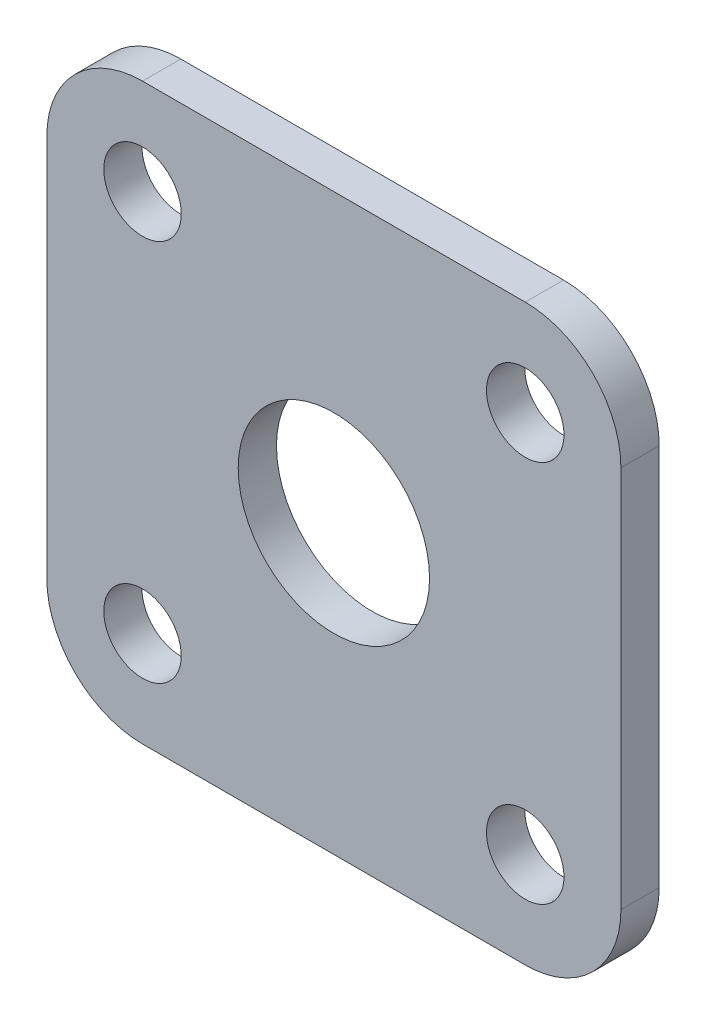
SolidWorks part; units mm, degrees
material "AISI 304"
ref_plane "Front Plane" through (0, 0, 0) normal (0, 0, 1) x (1, 0, 0)
ref_plane "Top Plane" through (0, 0, 0) normal (0, 1, 0) x (1, 0, 0)
ref_plane "Right Plane" through (0, 0, 0) normal (1, 0, 0) x (0, 0, -1)
sketch "Sketch1" plane through (0, 0, 0) normal (0, 0, 1) x (1, 0, 0)
  line L1 (-10, 15) -> (10, 15)
  line L2 (-15, 10) -> (-15, -10)
  line L3 (-10, -15) -> (10, -15)
  line L4 (15, 10) -> (15, -10)
  line L5 (-15, 15) -> (15, -15) construction
  line L6 (-15, -15) -> (15, 15) construction
  line L7 (-10, 10) -> (10, 10) construction
  line L8 (-10, 10) -> (-10, -10) construction
  line L9 (-10, -10) -> (10, -10) construction
  line L10 (10, 10) -> (10, -10) construction
  line L11 (-10, 10) -> (10, -10) construction
  line L12 (-10, -10) -> (10, 10) construction
  circle A0 centre (-10, 10) radius 2.025
  circle A1 centre (10, 10) radius 2.025
  circle A2 centre (10, -10) radius 2.025
  circle A3 centre (-10, -10) radius 2.025
  arc A4 (-15, -10) -> (-10, -15) centre (-10, -10) ccw
  arc A5 (10, -15) -> (15, -10) centre (10, -10) ccw
  arc A6 (10, 15) -> (15, 10) centre (10, 10) cw
  arc A7 (-10, 15) -> (-15, 10) centre (-10, 10) ccw
  circle A8 centre (0, 0) radius 5
  point P0 (0, 0)
  point P6 (0, 0)
  dimension "D5" = 4.05
  dimension "D6" = 4.05
  dimension "D7" = 4.05
  dimension "D8" = 4.05
  dimension "D9" = 5
  dimension "D10" = 10
  dimension "D1" = 30
  dimension "D2" = 30
  dimension "D3" = 20
  dimension "D4" = 20
extrude "Boss-Extrude1" add sketch "Sketch1" along normal blind 2
